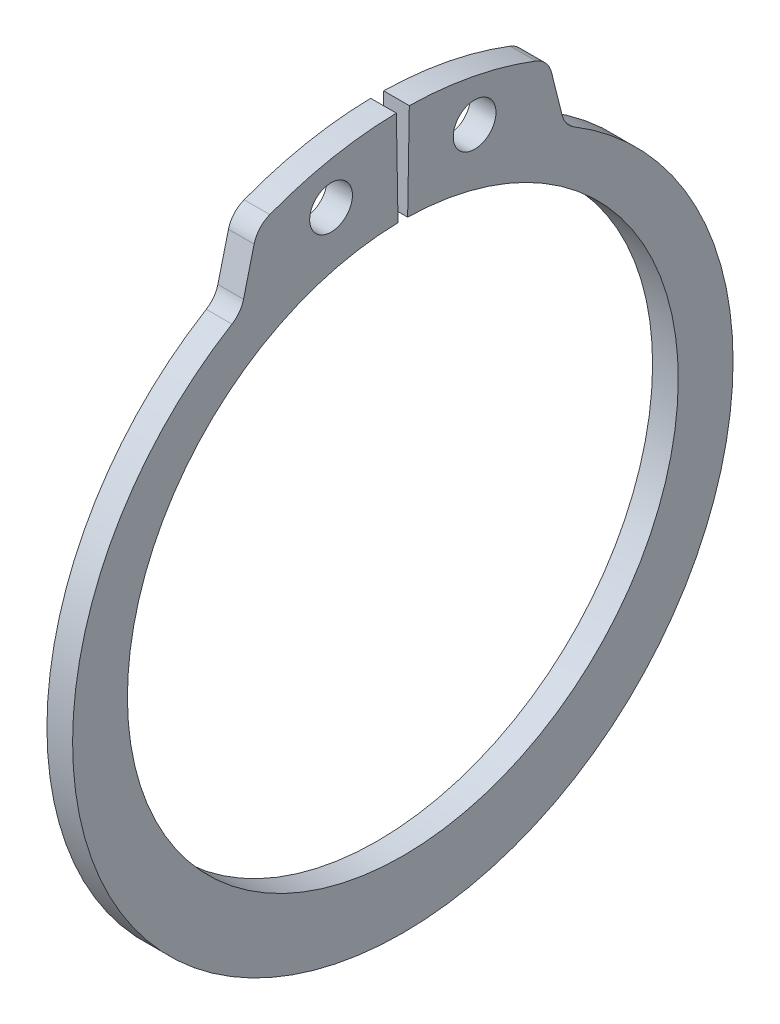
SolidWorks part; units mm, degrees
material "Cast Carbon Steel"
ref_plane "Front" through (0, 0, 0) normal (0, 0, 1) x (1, 0, 0)
ref_plane "Top" through (0, 0, 0) normal (0, 1, 0) x (1, 0, 0)
ref_plane "Right" through (0, 0, 0) normal (1, 0, 0) x (0, 0, -1)
sketch "Sketch1" plane through (0, 0, 0) normal (1, 0, 0) x (0, 0, -1)
  line L0 (0, 0) -> (0, 16.1) construction
  line L1 (-0.281, 16.0975) -> (-0.3787, 21.6967)
  line L2 (-0.3787, 21.6967) -> (-8.1096, 21.5618) construction
  line L3 (-8.1096, 21.5618) -> (-9.4644, 16.1281) construction
  line L4 (0.3787, 21.6967) -> (0.281, 16.0975)
  line L5 (0.3787, 21.6967) -> (8.1096, 21.5618) construction
  line L6 (8.1096, 21.5618) -> (9.4644, 16.1281) construction
  line L7 (-9.4644, 16.1281) -> (-8.1485, 13.8857) construction
  line L8 (9.4644, 16.1281) -> (8.1485, 13.8857) construction
  line L9 (0, -16.1) -> (0, -20) construction
  line L10 (-8.1096, 21.5618) -> (-0.281, 16.0975) construction
  line L11 (-16.1, 0) -> (16.1, 0) construction
  line L12 (0, 16.1) -> (0, 21.7) construction
  line L13 (8.5084, 19.9624) -> (9.4644, 16.1281)
  line L14 (-8.5084, 19.9624) -> (-9.4644, 16.1281)
  circle A0 centre (0, 0) radius 16.1 construction
  arc A1 (-0.281, 16.0975) -> (0.281, 16.0975) centre (0, 0) ccw
  circle A2 centre (0, -0.6963) radius 19.3037 construction
  circle A4 centre (-4.1953, 18.8296) radius 1.25
  circle A5 centre (4.1953, 18.8296) radius 1.25
  arc A6 (-9.4644, 16.1281) -> (9.4644, 16.1281) centre (0, -0.6963) ccw
  arc A7 (0.3787, 21.6967) -> (8.5084, 19.9624) centre (0, 0) cw
  arc A8 (-0.3787, 21.6967) -> (-8.5084, 19.9624) centre (0, 0) ccw
  dimension "A" = 32.2
  dimension "Hole" = 2.5
  dimension "Smin" = 2.6
  dimension "D1" = 75
  dimension "Angle" = 1
  dimension "H" = 5.6
extrude "Extrude1" add sketch "Sketch1" along normal mid plane 1.5
fillet "Fillet1" radius 1.5 4 edges at (0, 16.1281, 9.4644) (0, 19.9624, 8.5084) (0, 19.9624, -8.5084) (0, 16.1281, -9.4644)
sketch "Sketch2" plane through (0, 0, 0) normal (0, 0, 1) x (1, 0, 0)
  line L0 (-4, 0) -> (12, 0)
  line L1 (12, 0) -> (12, -17.5)
  line L2 (-4, 0) -> (-4, -16.5)
  line L3 (12, -17.5) -> (0.8, -17.5)
  line L4 (0.8, -17.5) -> (0.8, -16.5)
  line L5 (0.8, -16.5) -> (-0.8, -16.5)
  line L6 (-0.8, -16.5) -> (-0.8, -17.5)
  line L7 (-0.8, -17.5) -> (-4, -17.5) construction
  line L8 (-4, -17.5) -> (-4, 0) construction
  line L9 (0, -16.5) -> (0, 0) construction
  line L10 (12, 0) -> (14.0551, 0) construction
  line L11 (-4, -16.5) -> (-3, -17.5)
  line L12 (-3, -17.5) -> (-0.8, -17.5)
  dimension "D2" = 16
  dimension "D3" = 4
  dimension "D1" = 45
revolve "Revolve1" [suppressed] add sketch "Sketch2" angle 360 about L10
equation "\"D2@Sketch2\" = \"W@Sketch2\"*10"
equation "\"D3@Sketch2\" = \"D2@Sketch2\"/4"
equation "\"Smin@Sketch1\" = \"Smax@Sketch1\"/1.5"
equation "\"D1@Fillet1\" = \"D1@Extrude1\""
